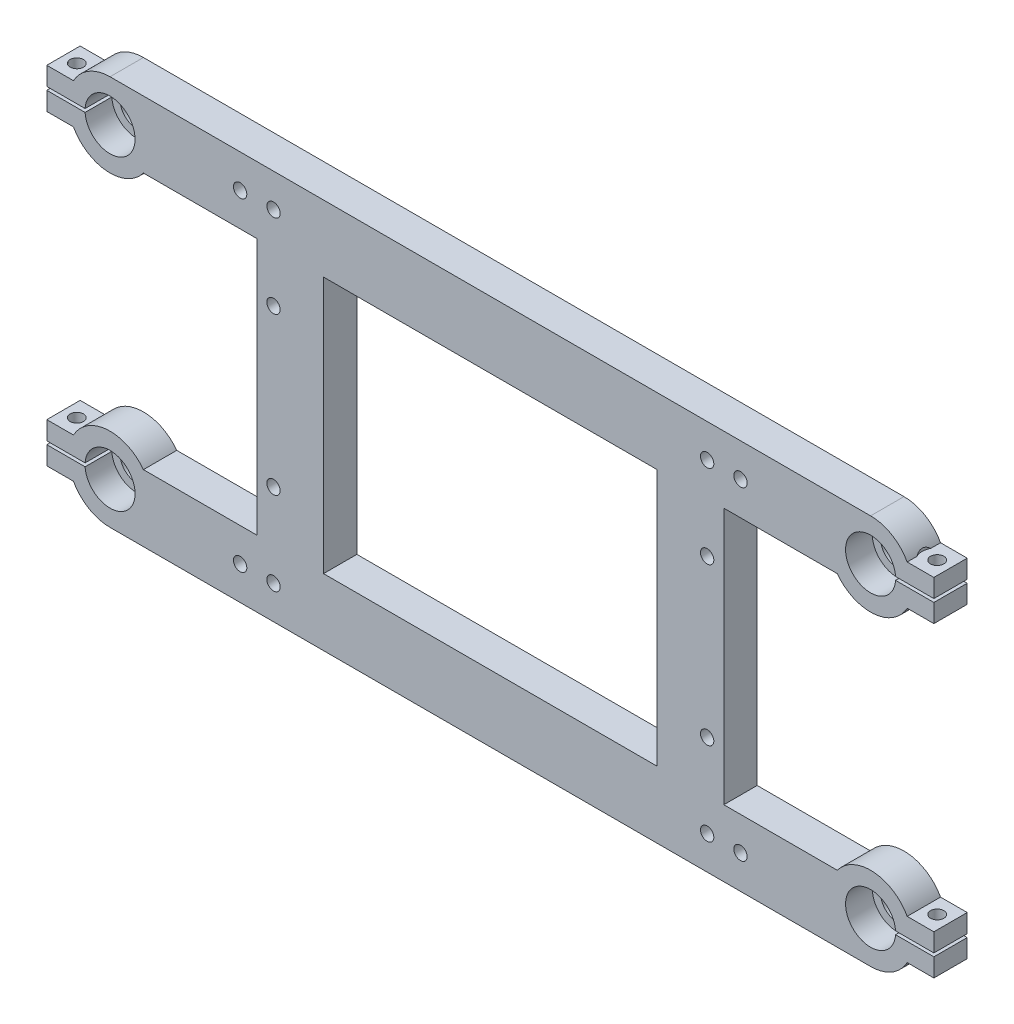
SolidWorks part; units mm, degrees
material "1060 合金"
ref_plane "前视基准面" through (0, 0, 0) normal (0, 0, 1) x (1, 0, 0)
ref_plane "上视基准面" through (0, 0, 0) normal (0, 1, 0) x (1, 0, 0)
ref_plane "右视基准面" through (0, 0, 0) normal (1, 0, 0) x (0, 0, -1)
sketch "草图1" plane through (0, 0, 0) normal (0, 0, 1) x (1, 0, 0)
  line L0 (-104, 84.5) -> (-70, 84.5)
  line L1 (-70, 84.5) -> (-70, 7.5)
  line L2 (-104, 7.5) -> (-70, 7.5)
  line L3 (-114, 104.5) -> (-64, 104.5)
  line L7 (114, -12.5) -> (-114, -12.5)
  line L8 (0, 151.6854) -> (0, -40.7139) construction
  line L9 (-64, 104.5) -> (64, 104.5)
  line L10 (-50, 84.5) -> (50, 84.5)
  line L11 (-50, 84.5) -> (-50, 7.5)
  line L12 (-50, 7.5) -> (50, 7.5)
  line L16 (50, 84.5) -> (50, 7.5)
  line L23 (114, 104.5) -> (64, 104.5)
  line L24 (104, 7.5) -> (70, 7.5)
  line L25 (70, 84.5) -> (70, 7.5)
  line L26 (104, 84.5) -> (70, 84.5)
  circle A0 centre (-114, 0) radius 5
  circle A1 centre (-114, 92) radius 5
  arc A2 (-114, 104.5) -> (-104, 84.5) centre (-114, 92) ccw
  arc A3 (-104, 7.5) -> (-114, -12.5) centre (-114, 0) ccw
  arc A8 (104, 7.5) -> (114, -12.5) centre (114, 0) cw
  arc A9 (114, 104.5) -> (104, 84.5) centre (114, 92) cw
  circle A10 centre (114, 92) radius 5
  circle A11 centre (114, 0) radius 5
  point P5 (0, -12.5)
  point P31 (0, 83.8883)
  point P32 (0, 103.8883)
  point P37 (0, 7.5)
  point P38 (0, 84.5)
  point P39 (0, 104.5)
  dimension "D1" = 10
  dimension "D3" = 25
  dimension "D2" = 92
  dimension "D4" = 50
  dimension "D5" = 20
  dimension "D6" = 70
  dimension "D7" = 20
  dimension "D8" = 228
  dimension "D9" = 20
extrude "凸台-拉伸1" add sketch "草图1" along normal blind 10
sketch "草图3" plane through (0, 0, 10) normal (0, 0, 1) x (1, 0, 0)
  line L0 (0, 111.1634) -> (0, -18.3618) construction
  circle A0 centre (-114, 92) radius 7.5
  circle A1 centre (-114, 0) radius 7.5
  circle A2 centre (-114, 0) radius 5 construction
  circle A3 centre (114, 0) radius 7.5
  circle A4 centre (114, 92) radius 7.5
  dimension "D1" = 15
extrude "切除-拉伸1" cut sketch "草图3" against normal offset from surface (8 mm away) 2 up to face at (109, 92, 0)
sketch "草图5" plane through (0, 0, 0) normal (0, 0, 1) x (1, 0, 0)
  line L0 (0, -12.5) -> (0, 104.5) construction
  line L1 (-114, -12.5) -> (114, -12.5) construction
  line L2 (114, 104.5) -> (-114, 104.5) construction
  line L3 (-70, 84.5) -> (-70, 7.5) construction
  circle A0 centre (-65, 94.5) radius 2
  circle A2 centre (-75, 94.5) radius 2
  circle A3 centre (-65, 69.5) radius 2
  circle A4 centre (-65, 22.5) radius 2
  circle A5 centre (-65, -2.5) radius 2
  circle A6 centre (-75, -2.5) radius 2
  circle A7 centre (75, -2.5) radius 2
  circle A8 centre (65, -2.5) radius 2
  circle A9 centre (65, 22.5) radius 2
  circle A10 centre (65, 69.5) radius 2
  circle A11 centre (75, 94.5) radius 2
  circle A12 centre (65, 94.5) radius 2
  dimension "D1" = 4
  dimension "D2" = 10
  dimension "D3" = 5
  dimension "D4" = 10
  dimension "D5" = 25
  dimension "D6" = 10
  dimension "D7" = 10
  dimension "D8" = 25
extrude "切除-拉伸2" cut sketch "草图5" along normal up to next
sketch "草图6" plane through (0, 0, 10) normal (0, 0, 1) x (1, 0, 0)
  line L0 (0, 104.5) -> (0, -12.5) construction
  line L1 (124.9659, 98) -> (132.9659, 98)
  line L2 (124.9659, 98) -> (124.9659, 86)
  line L3 (124.9659, 86) -> (132.9659, 86)
  line L4 (132.9659, 98) -> (132.9659, 86)
  line L5 (114, 104.5) -> (-114, 104.5) construction
  line L6 (-114, -12.5) -> (114, -12.5) construction
  line L7 (70, 46) -> (-70, 46) construction
  line L8 (70, 7.5) -> (70, 84.5) construction
  line L9 (-70, 84.5) -> (-70, 7.5) construction
  line L10 (132.9659, -6) -> (132.9659, 6)
  line L11 (124.9659, 6) -> (132.9659, 6)
  line L12 (124.9659, -6) -> (124.9659, 6)
  line L13 (124.9659, -6) -> (132.9659, -6)
  line L14 (-124.9659, -6) -> (-132.9659, -6)
  line L15 (-124.9659, -6) -> (-124.9659, 6)
  line L16 (-124.9659, 6) -> (-132.9659, 6)
  line L17 (-132.9659, -6) -> (-132.9659, 6)
  line L18 (-132.9659, 98) -> (-132.9659, 86)
  line L19 (-124.9659, 86) -> (-132.9659, 86)
  line L20 (-124.9659, 98) -> (-124.9659, 86)
  line L21 (-124.9659, 98) -> (-132.9659, 98)
  arc A0 (104, 84.5) -> (114, 104.5) centre (114, 92) ccw construction
  dimension "D1" = 8
  dimension "D2" = 12
extrude "凸台-拉伸2" add sketch "草图6" against normal up to surface (10 mm away) up to face at (-73, -2.5, 0)
sketch "草图7" plane through (0, 0, 10) normal (0, 0, 1) x (1, 0, 0)
  line L0 (0, -12.5) -> (0, 104.5) construction
  line L1 (-114, -12.5) -> (114, -12.5) construction
  line L2 (114, 104.5) -> (-114, 104.5) construction
  line L3 (70, 46) -> (-70, 46) construction
  line L4 (70, 7.5) -> (70, 84.5) construction
  line L5 (-70, 84.5) -> (-70, 7.5) construction
  line L6 (132.9659, 86) -> (132.9659, 98) construction
  line L7 (132.9659, 92.5) -> (117.9659, 92.5)
  line L8 (132.9659, 92.5) -> (132.9659, 91.5)
  line L9 (132.9659, 91.5) -> (117.9659, 91.5)
  line L10 (117.9659, 92.5) -> (117.9659, 91.5)
  line L11 (117.9659, -0.5) -> (117.9659, 0.5)
  line L12 (132.9659, 0.5) -> (117.9659, 0.5)
  line L13 (132.9659, -0.5) -> (132.9659, 0.5)
  line L14 (132.9659, -0.5) -> (117.9659, -0.5)
  line L15 (-132.9659, -0.5) -> (-117.9659, -0.5)
  line L16 (-132.9659, -0.5) -> (-132.9659, 0.5)
  line L17 (-132.9659, 0.5) -> (-117.9659, 0.5)
  line L18 (-117.9659, -0.5) -> (-117.9659, 0.5)
  line L19 (-117.9659, 92.5) -> (-117.9659, 91.5)
  line L20 (-132.9659, 91.5) -> (-117.9659, 91.5)
  line L21 (-132.9659, 92.5) -> (-132.9659, 91.5)
  line L22 (-132.9659, 92.5) -> (-117.9659, 92.5)
  point P20 (132.9659, 92)
  point P21 (132.9659, 92)
  dimension "D1" = 1
  dimension "D2" = 15
extrude "切除-拉伸3" cut sketch "草图7" against normal through all
sketch "草图8" plane through (0, 98, 0) normal (0, 1, 0) x (1, 0, 0)
  line L0 (-132.9659, 0) -> (-132.9659, -10) construction
  line L1 (0, 0) -> (0, -10) construction
  line L2 (114, -10) -> (-114, -10) construction
  circle A0 centre (-128.9659, -5) radius 2
  circle A1 centre (128.9659, -5) radius 2
  point P5 (-132.9659, -5)
  dimension "D1" = 4
  dimension "D2" = 4
extrude "切除-拉伸4" cut sketch "草图8" against normal through all
sketch "草图9" plane through (0, 98, 0) normal (0, 1, 0) x (1, 0, 0)
  line L0 (0, 0) -> (0, -10) construction
  line L1 (114, -10) -> (-114, -10) construction
  circle A0 centre (-128.9659, -5) radius 4.5
  circle A1 centre (128.9659, -5) radius 4.5
  dimension "D1" = 9
extrude "切除-拉伸5" cut sketch "草图9" along normal blind 10
chamfer "倒角1" distance 2 angle 45 12 edges at (-73, 94.5, 0) (-63, 94.5, 0) (-63, 69.5, 0) (-63, 22.5, 0) (-63, -2.5, 0) (-73, -2.5, 0) (73, -2.5, 0) (63, -2.5, 0) (63, 22.5, 0) (63, 69.5, 0) (63, 94.5, 0) (73, 94.5, 0)
